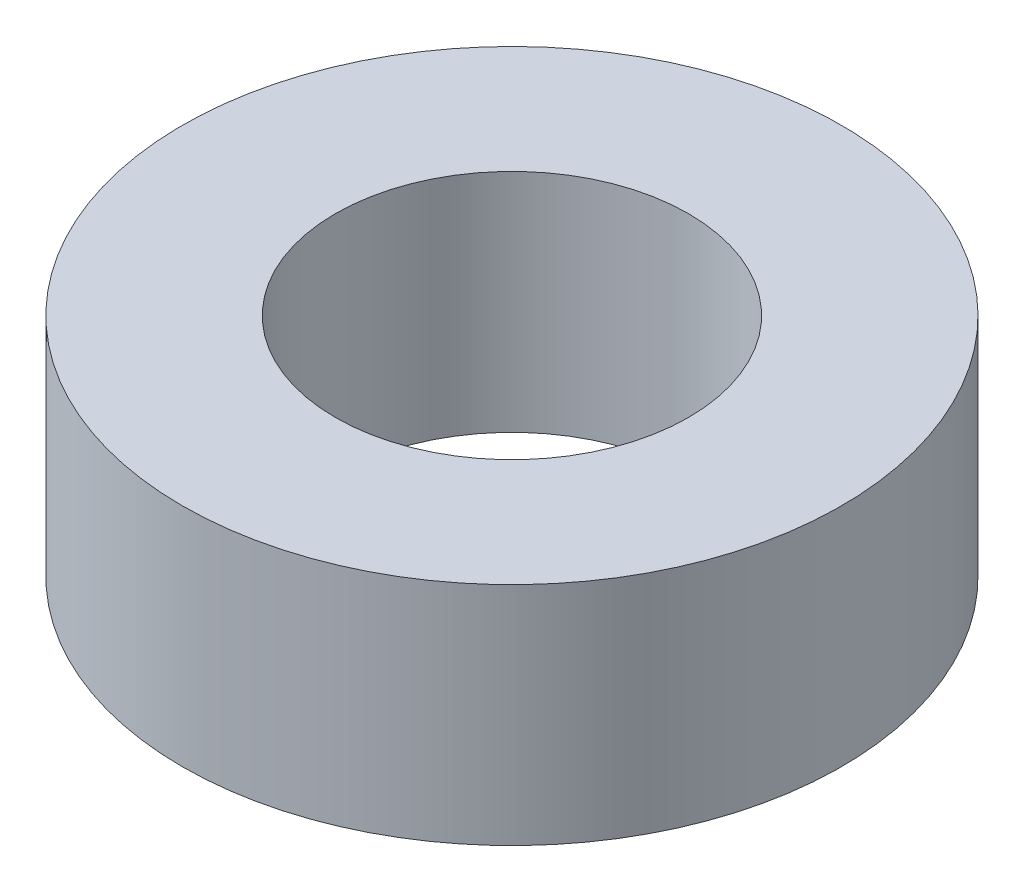
SolidWorks part; units mm, degrees
ref_plane "Front Plane" through (0, 0, 0) normal (0, 0, 1) x (1, 0, 0)
ref_plane "Top Plane" through (0, 0, 0) normal (0, 1, 0) x (1, 0, 0)
ref_plane "Right Plane" through (0, 0, 0) normal (1, 0, 0) x (0, 0, -1)
ref_plane "Plane1"
sketch "Sketch1" plane through (0, 0, 0) normal (0, 1, 0) x (-1, 0, 0)
  circle A0 centre (0, 0) radius 7
  circle A1 centre (0, 0) radius 3.75
  dimension "D1" = 7.5
  dimension "D2" = 14
extrude "Extrusion1" add sketch "Sketch1" along normal blind 4.8 contours A0 A1
